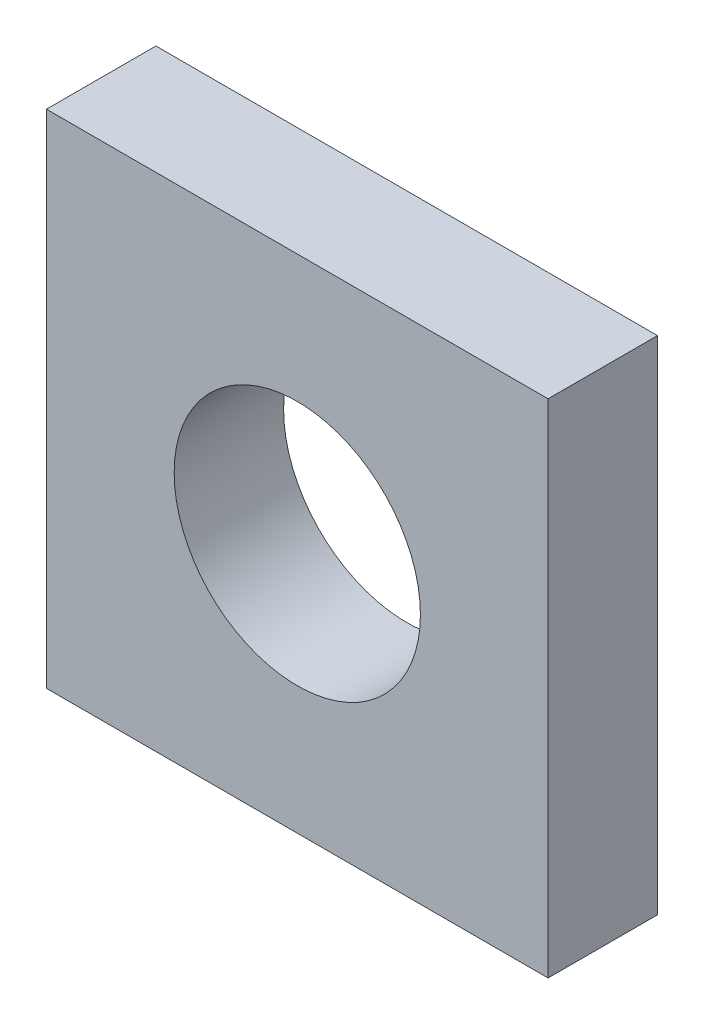
SolidWorks part; units mm, degrees
material "1023 Chapa de aço carbono (SS)"
ref_plane "Plano frontal" through (0, 0, 0) normal (0, 0, 1) x (1, 0, 0)
ref_plane "Plano superior" through (0, 0, 0) normal (0, 1, 0) x (1, 0, 0)
ref_plane "Plano direito" through (0, 0, 0) normal (1, 0, 0) x (0, 0, -1)
sketch "Esboço1" plane through (0, 0, 0) normal (0, 0, 1) x (1, 0, 0)
  line L0 (0, 0) -> (0, 2.75) construction
  line L1 (-2.75, 2.75) -> (2.75, 2.75)
  line L2 (-2.75, 2.75) -> (-2.75, -2.75)
  line L3 (-2.75, -2.75) -> (2.75, -2.75)
  line L4 (2.75, 2.75) -> (2.75, -2.75)
  line L5 (0, 0) -> (2.75, 0) construction
  circle A0 centre (0, 0) radius 1.35
  dimension "D3" = 2.7
  dimension "D1" = 5.5
  dimension "D2" = 5.5
extrude "Ressalto-extrusão1" add sketch "Esboço1" along normal mid plane 1.2
cosmetic thread "Representação de rosca1" parameters "D2"=3
